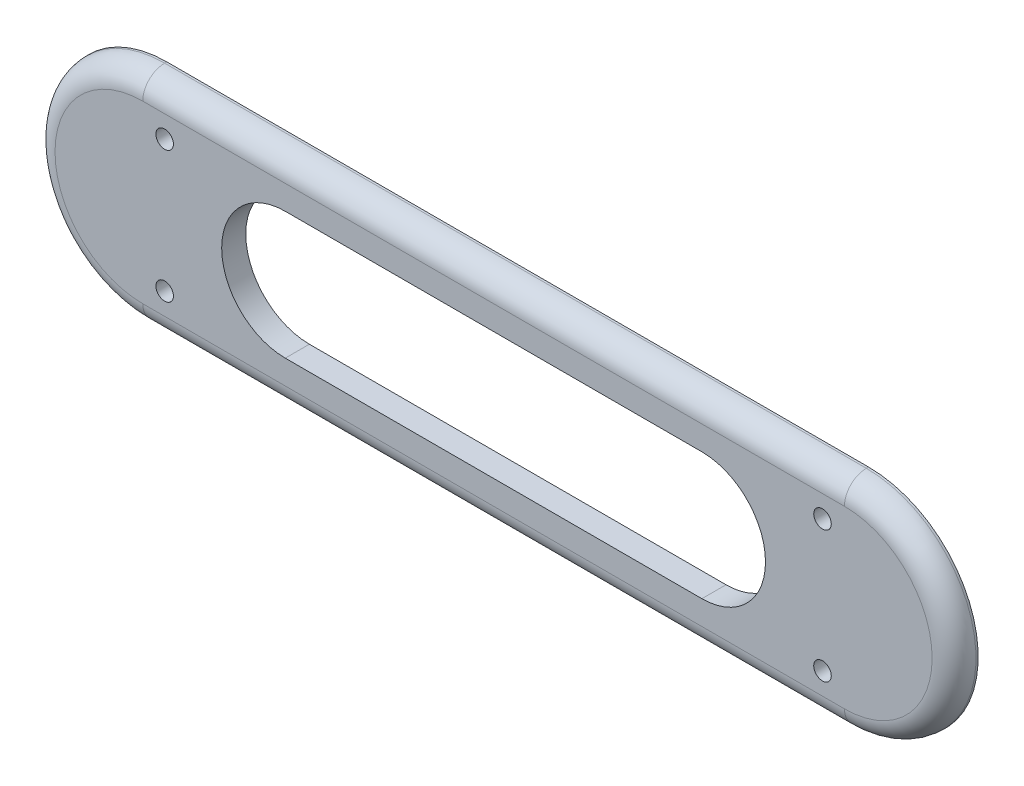
SolidWorks part; units mm, degrees
ref_plane "Front Plane" through (0, 0, 0) normal (0, 0, 1) x (1, 0, 0)
ref_plane "Top Plane" through (0, 0, 0) normal (0, 1, 0) x (1, 0, 0)
ref_plane "Right Plane" through (0, 0, 0) normal (1, 0, 0) x (0, 0, -1)
sketch "Sketch1" plane through (0, 0, 0) normal (0, 0, 1) x (1, 0, 0)
  line L0 (0, 0) -> (-80, 0) construction
  line L1 (0, 0) -> (0, 14.5) construction
  line L2 (-47.5, 14.5) -> (47.5, 14.5)
  line L3 (-47.5, -14.5) -> (47.5, -14.5)
  line L13 (-77, 15) -> (-75, 15) construction
  line L14 (-47.5, 0) -> (-47.5, -14.5) construction
  line L18 (-47.5, -58) -> (-47.5, -60) construction
  line L19 (-80, -25) -> (80, -25)
  line L20 (-80, 25) -> (80, 25)
  arc A0 (-47.5, 14.5) -> (-47.5, -14.5) centre (-47.5, 0) ccw
  arc A1 (47.5, 14.5) -> (47.5, -14.5) centre (47.5, 0) cw
  circle A2 centre (-75, 15) radius 2
  circle A3 centre (-75, -15) radius 2
  circle A6 centre (75, -15) radius 2
  circle A7 centre (75, 15) radius 2
  arc A10 (-80, -25) -> (-80, 25) centre (-80, 0) cw
  arc A11 (80, -25) -> (80, 25) centre (80, 0) ccw
  point P8 (0, -14.5)
  point P16 (0, 25)
  dimension "D2" = 29
  dimension "D11" = 4
  dimension "D1" = 47.5
  dimension "D3" = 14.5
  dimension "D4" = 80
  dimension "D12" = 60
extrude "Boss-Extrude2" add sketch "Sketch1" along normal blind 5.5
fillet "Fillet1" radius 5 4 edges at (105, 0, 5.5) (0, -25, 5.5) (-105, 0, 5.5) (0, 25, 5.5)
